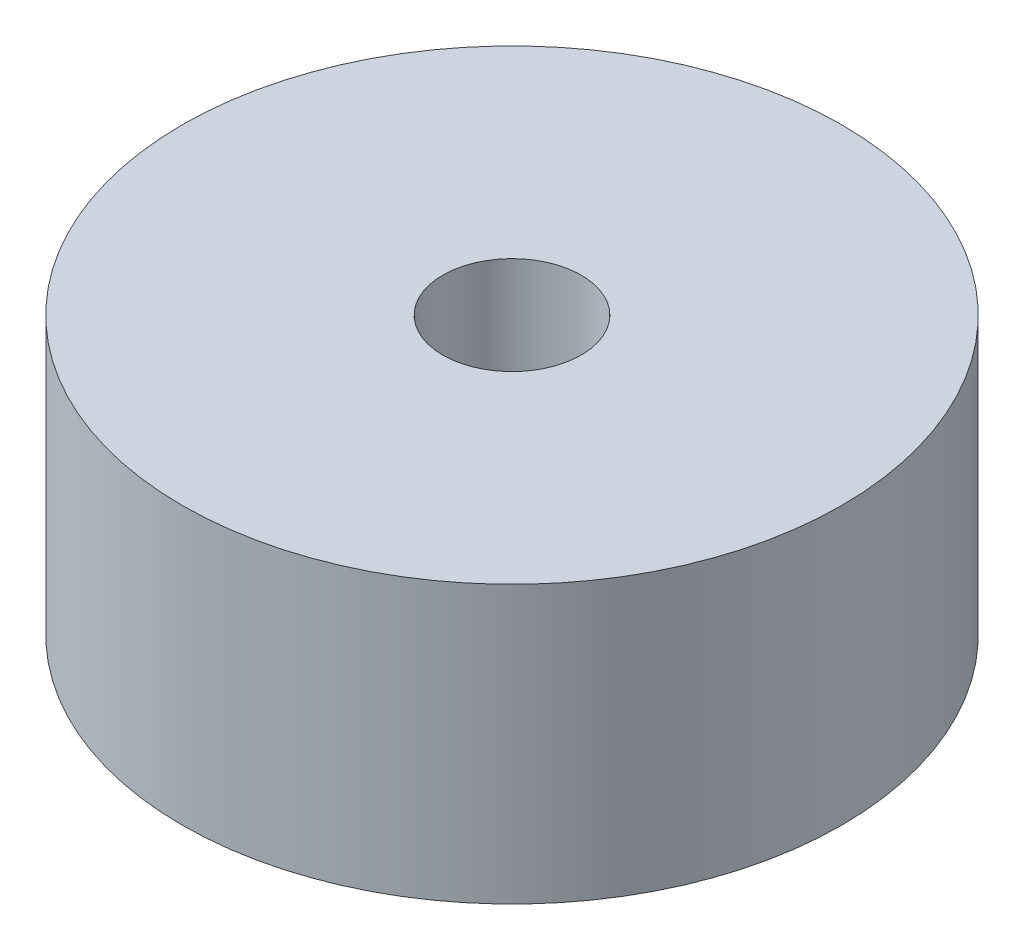
SolidWorks part; units mm, degrees
material "ABS"
ref_plane "Front Plane" through (0, 0, 0) normal (0, 0, 1) x (1, 0, 0)
ref_plane "Top Plane" through (0, 0, 0) normal (0, 1, 0) x (1, 0, 0)
ref_plane "Right Plane" through (0, 0, 0) normal (1, 0, 0) x (0, 0, -1)
sketch "Sketch1" plane through (0, 0, 0) normal (0, 1, 0) x (1, 0, 0)
  circle A0 centre (0, 0) radius 9.525
  circle A1 centre (0, 0) radius 2
  dimension "D1" = 19.05
  dimension "D2" = 4
extrude "Boss-Extrude1" add sketch "Sketch1" along normal blind 8
